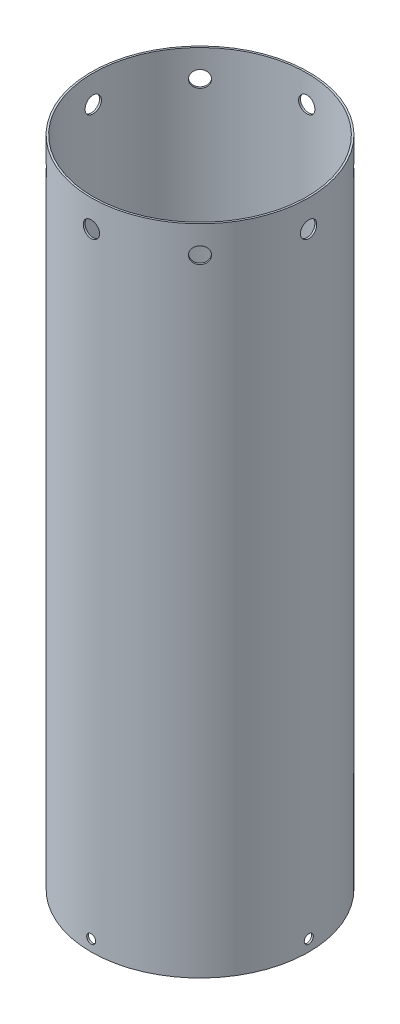
SolidWorks part; units mm, degrees
ref_plane "Front Plane" through (0, 0, 0) normal (0, 0, 1) x (1, 0, 0)
ref_plane "Top Plane" through (0, 0, 0) normal (0, 1, 0) x (1, 0, 0)
ref_plane "Right Plane" through (0, 0, 0) normal (1, 0, 0) x (0, 0, -1)
sketch "Sketch1" plane through (0, 0, 0) normal (0, 1, 0) x (1, 0, 0)
  circle A0 centre (0, 0) radius 76.2
  dimension "D1" = 152.4
extrude "Boss-Extrude1" add sketch "Sketch1" along normal blind 457.2
sketch "Sketch2" plane through (0, 457.2, 0) normal (0, 1, 0) x (1, 0, 0)
  circle A0 centre (0, 0) radius 74.93
  dimension "D1" = 149.86
extrude "Cut-Extrude1" cut sketch "Sketch2" against normal through all
sketch "Sketch3" plane through (0, 0, 0) normal (0, 0, 1) x (1, 0, 0)
  line L0 (0, 457.2) -> (0, 438.15)
  line L1 (76.2, 457.2) -> (-76.2, 457.2) construction
  circle A0 centre (0, 438.15) radius 5.715
  dimension "D1" = 19.05
  dimension "D2" = 11.43
extrude "Cut-Extrude2" cut sketch "Sketch3" against normal through all both and the other way through all contours A0
pattern_circular "CirPattern1" count 8 over 360 about axis through (0, 457.2, 0) along (0, -1, 0) of "Cut-Extrude2"
sketch "Sketch4" plane through (0, 0, 0) normal (0, 0, 1) x (1, 0, 0)
  line L0 (0, 0) -> (0, 7.9375)
  line L1 (-76.2, 0) -> (76.2, 0) construction
  circle A0 centre (0, 7.9375) radius 3.175
extrude "Cut-Extrude3" cut sketch "Sketch4" against normal through all both and the other way through all contours A0
pattern_circular "CirPattern2" count 4 over 360 about axis through (0, 457.2, 0) along (0, -1, 0) of "Cut-Extrude3"
